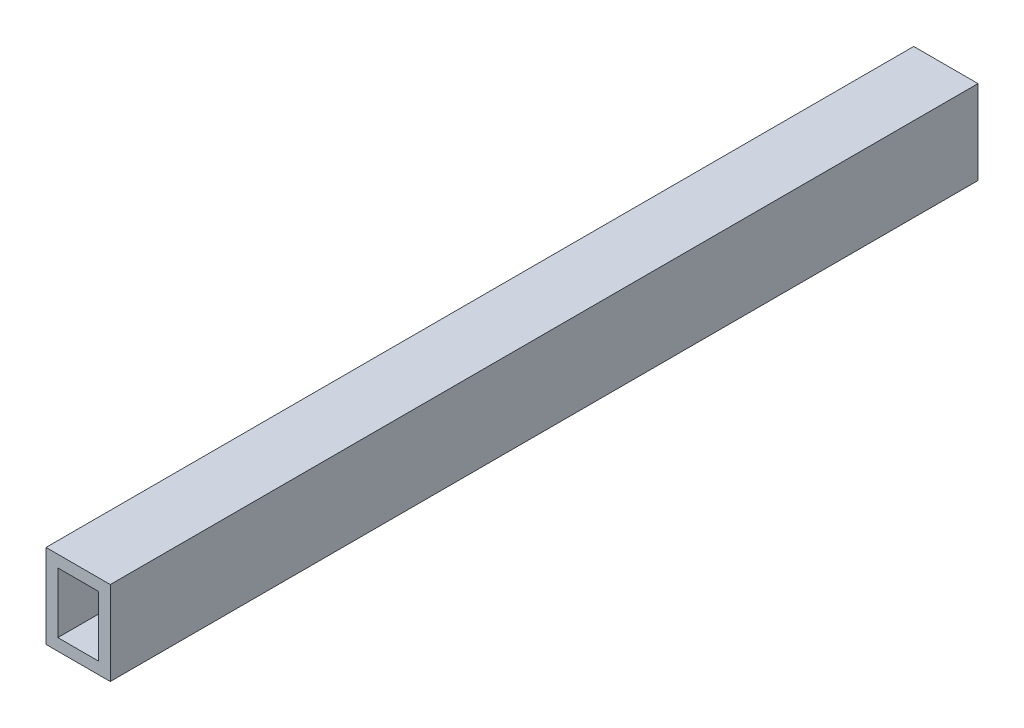
SolidWorks part; units mm, degrees
ref_plane "前视基准面" through (0, 0, 0) normal (0, 0, 1) x (1, 0, 0)
ref_plane "上视基准面" through (0, 0, 0) normal (0, 1, 0) x (1, 0, 0)
ref_plane "右视基准面" through (0, 0, 0) normal (1, 0, 0) x (0, 0, -1)
other "Configuration Table"
sketch "草图1" plane through (0, 0, 0) normal (0, 0, 1) x (1, 0, 0)
  line L0 (-5.15, 7.65) -> (5.15, 7.65)
  line L1 (-5, 7.5) -> (5, 7.5) construction
  line L2 (-5, 7.5) -> (-5, -7.5) construction
  line L3 (-5, -7.5) -> (5, -7.5) construction
  line L4 (5, 7.5) -> (5, -7.5) construction
  line L5 (0, -7.5) -> (0, 7.5) construction
  line L6 (-5, 0) -> (5, 0) construction
  line L7 (5.15, 7.65) -> (5.15, -7.65)
  line L8 (-5.15, -7.65) -> (5.15, -7.65)
  line L9 (-5.15, 7.65) -> (-5.15, -7.65)
  line L10 (-8.15, 10.65) -> (8.15, 10.65)
  line L11 (8.15, 10.65) -> (8.15, -10.65)
  line L12 (-8.15, -10.65) -> (8.15, -10.65)
  line L13 (-8.15, 10.65) -> (-8.15, -10.65)
  point P0 (0, 0)
  dimension "D1" = 15
  dimension "D2" = 10
  dimension "D3" = 0.15
  dimension "D4" = 3
extrude "凸台-拉伸1" add sketch "草图1" along normal blind 220
